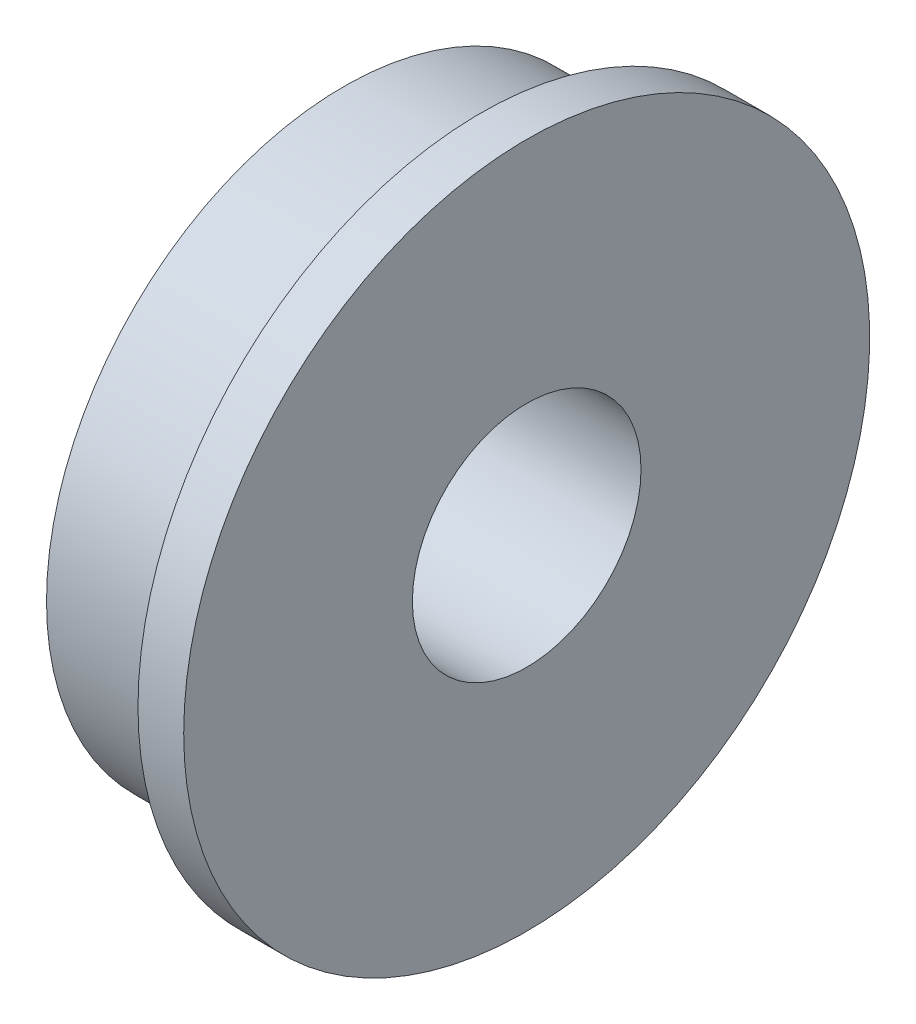
SolidWorks part; units mm, degrees
material "普通碳钢"
ref_plane "前视基准面" through (0, 0, 0) normal (0, 0, 1) x (1, 0, 0)
ref_plane "上视基准面" through (0, 0, 0) normal (0, 1, 0) x (1, 0, 0)
ref_plane "右视基准面" through (0, 0, 0) normal (1, 0, 0) x (0, 0, -1)
sketch "草图1" plane through (0, 0, 0) normal (0, 1, 0) x (1, 0, 0)
  line L0 (0, 0) -> (0, 7.2698) construction
  line L1 (0, 0) -> (12.184, 0) construction
  line L2 (4, 2.5) -> (4, 7.5)
  line L3 (4, 7.5) -> (3, 7.5)
  line L4 (3, 7.5) -> (3, 6.5)
  line L5 (3, 6.5) -> (0, 6.5)
  line L6 (0, 6.5) -> (0, 2.5)
  line L7 (0, 2.5) -> (4, 2.5)
  dimension "D1" = 1
  dimension "D2" = 13
  dimension "D3" = 5
  dimension "D4" = 4
  dimension "D5" = 1
revolve "旋转1" add sketch "草图1" angle 360 about L1
